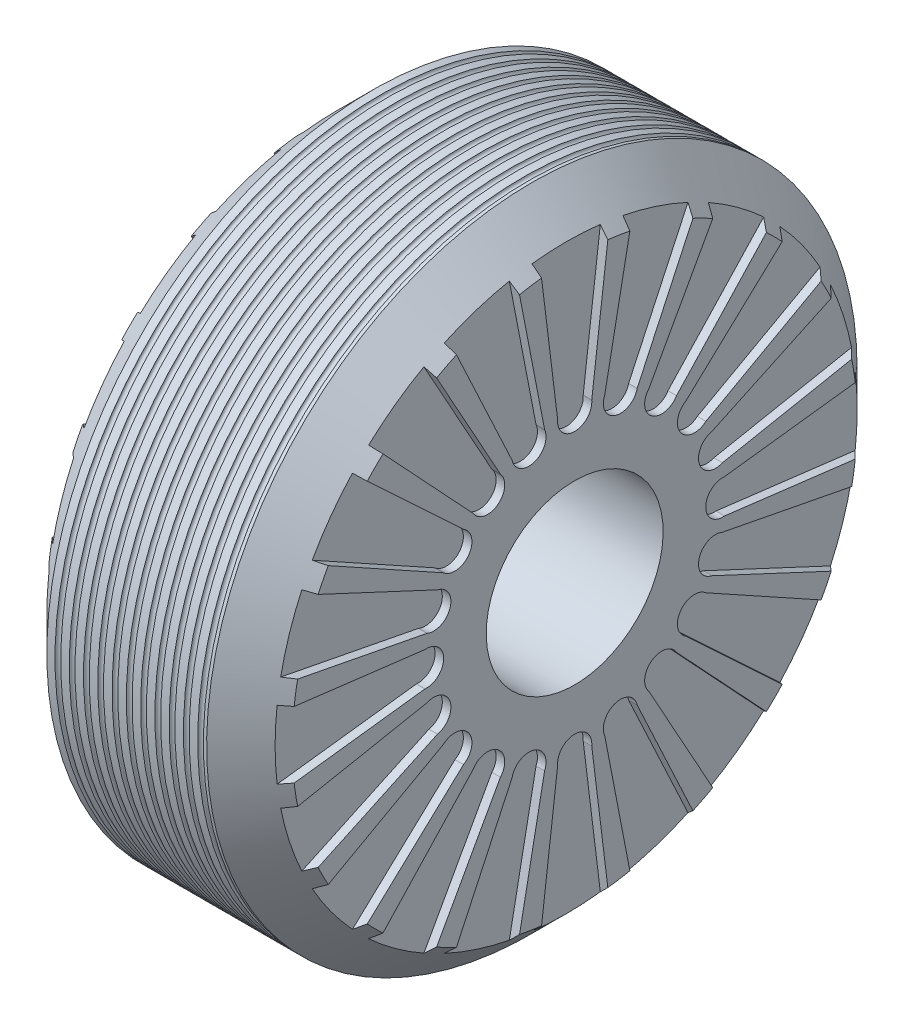
SolidWorks part; units mm, degrees
ref_plane "Front Plane" through (0, 0, 0) normal (0, 0, 1) x (1, 0, 0)
ref_plane "Top Plane" through (0, 0, 0) normal (0, 1, 0) x (1, 0, 0)
ref_plane "Right Plane" through (0, 0, 0) normal (1, 0, 0) x (0, 0, -1)
sketch "Sketch1" plane through (0, 0, 0) normal (1, 0, 0) x (0, 0, -1)
  circle A0 centre (0, 0) radius 114
  dimension "D1" = 228
extrude "Boss-Extrude2" add sketch "Sketch1" along normal blind 86
chamfer "Chamfer1" distance 15 angle 45 2 edges at (0, 0, -114) (86, 0, -114)
sketch "Sketch2" plane through (86, 0, 0) normal (1, 0, 0) x (0, 0, -1)
  line L0 (0, 0) -> (0, 105.5) construction
  line L1 (12.5, 105.5) -> (-12.5, 105.5)
  line L2 (-12.5, 105.5) -> (-5.9726, 52.5)
  line L3 (12.5, 105.5) -> (5.9726, 52.5)
  arc A0 (-5.9726, 52.5) -> (5.9726, 52.5) centre (0, 51.9275) ccw
  dimension "D3" = 6
  dimension "D1" = 105.5
  dimension "D2" = 53
  dimension "D4" = 53.5725
  dimension "D5" = 25
extrude "Cut-Extrude1" cut sketch "Sketch2" against normal blind 3
pattern_circular "CirPattern1" count 20 over 360 about axis through (0, 0, 0) along (1, 0, 0) of "Cut-Extrude1"
ref_plane "Plane2" through (43, 0, 0) normal (-1, 0, 0) x (0, 0, 1)
mirror "Mirror3" about plane through (43, 0, 0) normal (-1, 0, 0) of "CirPattern1", "Cut-Extrude1"
sketch "Sketch3" plane through (0, 0, 0) normal (0, 0, 1) x (1, 0, 0)
  line L0 (71, 114) -> (15, 114) construction
  line L2 (42.8664, 114) -> (44.8664, 114)
  arc A0 (42.8664, 114) -> (44.8664, 114) centre (43.8664, 114) ccw
  dimension "D1" = 1
revolve "Cut-Revolve3" cut sketch "Sketch3" angle 360 about axis through (86, 0, 0) along (-1, 0, 0)
pattern_linear "LPattern3" count 6 spacing 5 along (-1, 0, 0) count 6 spacing 5 along (1, 0, 0) of "Cut-Revolve3"
sketch "Sketch6" plane through (0, 0, 0) normal (0, 0, 1) x (1, 0, 0)
  line L0 (0, 31) -> (7, 31)
  line L1 (7, 44) -> (16.5, 44)
  line L2 (7, 31) -> (7, 44)
  line L3 (86, -6) -> (86, 6) construction
  line L4 (0, 0) -> (0, 98.3163) construction
  line L7 (16.5, 44) -> (19.8664, 40.6336)
  line L8 (19.8664, 114) -> (19.8664, -114) construction
  line L9 (19.8664, 40.6336) -> (19.8664, 31)
  line L10 (19.8664, 31) -> (86, 31)
  line L12 (86, 31) -> (86, 0)
  line L14 (86, 0) -> (0, 0)
  line L15 (0, 31) -> (0, 0)
  point P4 (7, 37.5)
  dimension "D1" = 135
  dimension "D2" = 37.5
  dimension "D3" = 31
  dimension "D4" = 7
  dimension "D5" = 3.3664
revolve "Cut-Revolve5" cut sketch "Sketch6" angle 360 about L14
sketch "Sketch7" plane through (0, 0, 0) normal (-1, 0, 0) x (0, 0, 1)
  circle A0 centre (0, 0) radius 37.5 construction
  circle A1 centre (0, 37.5) radius 4
  circle A2 centre (32.476, 18.75) radius 4
  circle A3 centre (32.476, -18.75) radius 4
  circle A4 centre (0, -37.5) radius 4
  circle A5 centre (-32.476, -18.75) radius 4
  circle A6 centre (-32.476, 18.75) radius 4
  point P18 (0, 0)
  dimension "D1" = 75
  dimension "D2" = 8
  dimension "D3" = 6
extrude "Cut-Extrude3" cut sketch "Sketch7" against normal blind 10
sketch "Sketch8" plane through (0, 0, 0) normal (0, 0, 1) x (1, 0, 0)
  line L0 (-62.1286, 0) -> (137.8714, 0) construction
  dimension "D1" = 200
